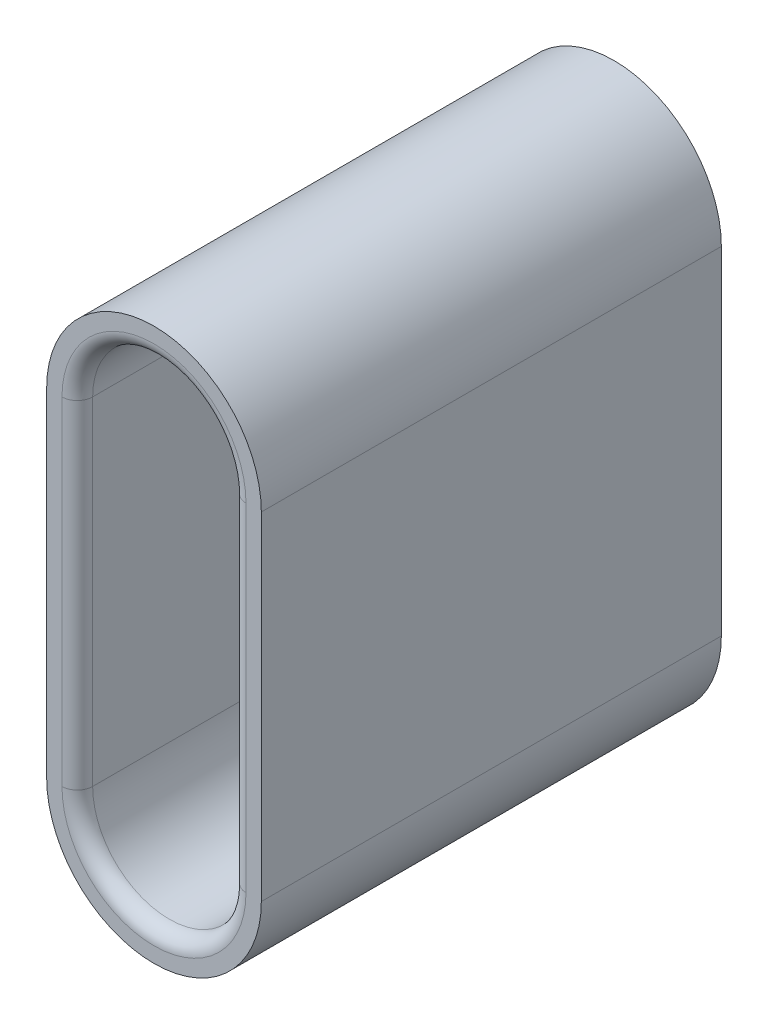
SolidWorks part; units mm, degrees
ref_plane "Front Plane" through (0, 0, 0) normal (0, 0, 1) x (1, 0, 0)
ref_plane "Top Plane" through (0, 0, 0) normal (0, 1, 0) x (1, 0, 0)
ref_plane "Right Plane" through (0, 0, 0) normal (1, 0, 0) x (0, 0, -1)
sketch "Sketch1" plane through (0, 0, 0) normal (0, 0, 1) x (1, 0, 0)
  line L0 (0, 0) -> (0, 11)
  line L2 (7, 11) -> (7, 0)
  arc A0 (7, 11) -> (0, 11) centre (3.5, 11) ccw
  arc A1 (0, 0) -> (7, 0) centre (3.5, 0) ccw
  dimension "D2" = 7
  dimension "D1" = 11
extrude "Boss-Extrude1" add sketch "Sketch1" along normal blind 15
sketch "Sketch2" plane through (0, 0, 15) normal (0, 0, 1) x (1, 0, 0)
  line L4 (6, 0) -> (6, 11)
  line L5 (1, 11) -> (1, 0)
  line L6 (6, 0) -> (6, 11)
  line L7 (1, 11) -> (1, 0)
  arc A4 (1, 0) -> (6, 0) centre (3.5, 0) ccw
  arc A5 (6, 11) -> (1, 11) centre (3.5, 11) ccw
  arc A6 (1, 0) -> (6, 0) centre (3.5, 0) ccw
  arc A7 (6, 11) -> (1, 11) centre (3.5, 11) ccw
  dimension "D1" = 1
extrude "Cut-Extrude1" cut sketch "Sketch2" against normal through all
fillet "Fillet1" radius 0.5 8 edges at (3.5, 13.5, 0) (6, 5.5, 0) (3.5, -2.5, 0) (3.5, 13.5, 15) (6, 5.5, 15) (3.5, -2.5, 15) (1, 5.5, 0) (1, 5.5, 15)
